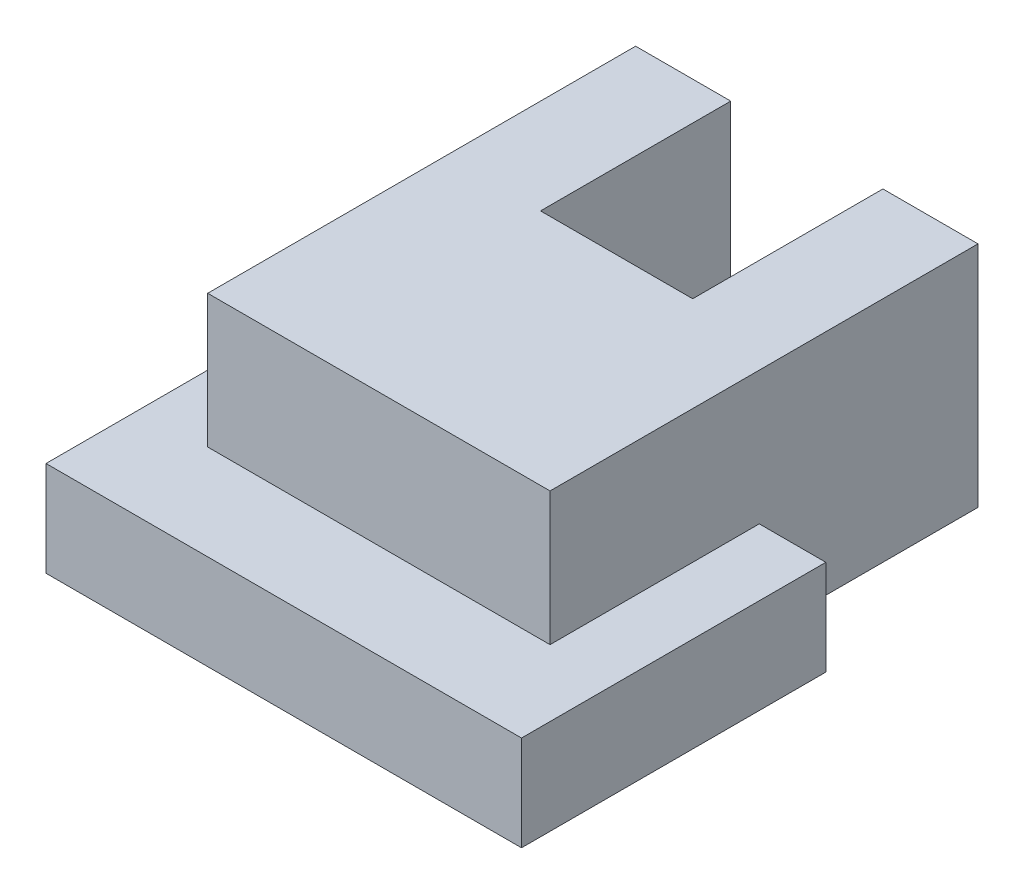
SolidWorks part; units mm, degrees
ref_plane "Alzado" through (0, 0, 0) normal (0, 0, 1) x (1, 0, 0)
ref_plane "Planta" through (0, 0, 0) normal (0, 1, 0) x (1, 0, 0)
ref_plane "Vista lateral" through (0, 0, 0) normal (1, 0, 0) x (0, 0, -1)
sketch "Croquis1" plane through (0, 0, 0) normal (0, 1, 0) x (1, 0, 0)
  line L1 (-25, 16) -> (25, 16)
  line L2 (-25, 16) -> (-25, -16)
  line L3 (-25, -16) -> (25, -16)
  line L4 (25, 16) -> (25, -16)
  line L5 (-25, 16) -> (25, -16) construction
  line L6 (-25, -16) -> (25, 16) construction
  point P0 (0, 0)
  dimension "D1" = 50
  dimension "D2" = 32
extrude "Saliente-Extruir1" add sketch "Croquis1" along normal blind 10
sketch "Croquis2" plane through (0, 10, 0) normal (0, 1, 0) x (1, 0, 0)
  line L0 (25, 16) -> (-25, 16) construction
  line L1 (-8, 39) -> (-18, 39)
  line L2 (18, 39) -> (8, 39)
  line L3 (18, 39) -> (18, -6)
  line L4 (18, -6) -> (-18, -6)
  line L5 (-18, 39) -> (-18, -6)
  line L7 (-8, 39) -> (-8, 19)
  line L8 (-8, 19) -> (8, 19)
  line L9 (8, 39) -> (8, 19)
  point P0 (0, -6)
  point P12 (0, 19)
  dimension "D1" = 45
  dimension "D2" = 36
  dimension "D3" = 22
  dimension "D4" = 16
  dimension "D5" = 20
extrude "Saliente-Extruir4" add sketch "Croquis2" along normal blind 14 and the other way up to surface other way up to face at (0, 0, 0)
